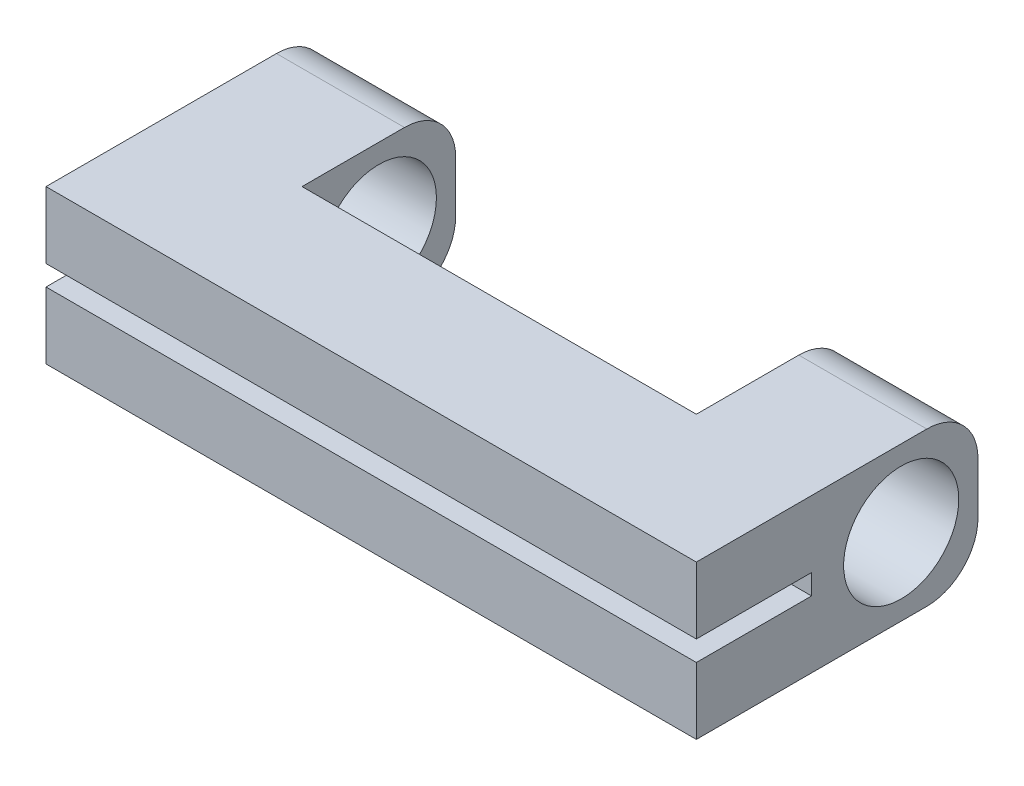
SolidWorks part; units mm, degrees
ref_plane "Front Plane" through (0, 0, 0) normal (0, 0, 1) x (1, 0, 0)
ref_plane "Top Plane" through (0, 0, 0) normal (0, 1, 0) x (1, 0, 0)
ref_plane "Right Plane" through (0, 0, 0) normal (1, 0, 0) x (0, 0, -1)
sketch "Sketch1" plane through (0, 0, 0) normal (0, 1, 0) x (1, 0, 0)
  line L1 (12.7, -2.5) -> (-12.7, -2.5)
  line L2 (12.7, -2.5) -> (12.7, 2.5)
  line L3 (12.7, 2.5) -> (-12.7, 2.5)
  line L4 (-12.7, -2.5) -> (-12.7, 2.5)
  line L5 (12.7, -2.5) -> (-12.7, 2.5) construction
  line L6 (12.7, 2.5) -> (-12.7, -2.5) construction
  point P0 (0, 0)
  dimension "D1" = 25.4
  dimension "D2" = 5
extrude "Boss-Extrude1" add sketch "Sketch1" along normal blind 6
sketch "Sketch2" plane through (12.7, 0, 0) normal (1, 0, 0) x (0, 0, -1)
  line L0 (-2.5, 6) -> (-2.5, 0) construction
  line L1 (-7, 2.6031) -> (2, 2.6031)
  line L2 (-7, 2.6031) -> (-7, 3.3969)
  line L3 (-7, 3.3969) -> (2, 3.3969)
  line L4 (2, 2.6031) -> (2, 3.3969)
  line L5 (-7, 2.6031) -> (2, 3.3969) construction
  line L6 (-7, 3.3969) -> (2, 2.6031) construction
  point P0 (-2.5, 3)
  dimension "D1" = 2
  dimension "D2" = 0.7937
extrude "Cut-Extrude1" cut sketch "Sketch2" against normal through all
sketch "Sketch3" plane through (0, 6, 0) normal (0, 1, 0) x (1, 0, 0)
  line L0 (6.35, 0) -> (-6.35, 0)
  point P4 (0, 0)
  dimension "D1" = 12.7
hole_wizard "M2 Clearance Hole1" positions "Sketch4" profile "Sketch5" hole size "M2" standard "ANSI Metric"
sketch "Sketch4" plane through (0, 6, 0) normal (0, 1, 0) x (1, 0, 0)
  point P0 (-6.35, 0)
  point P3 (6.35, 0)
sketch "Sketch5" plane through (-6.35, 6, 0) normal (1, 0, 0) x (0, 0, 1)
  line L0 (0, 0) -> (0, 6)
  line L1 (0, 6) -> (1.2, 6)
  line L2 (1.2, 6) -> (1.2, 0)
  line L5 (1.2, 0) -> (0, 0)
  line L11 (0, -6.35) -> (0, 107.95) construction
  dimension "Thru Hole Dia." = 2.4
  dimension "Thru Hole Depth" = 6
sketch "Sketch6" plane through (0, 0, -2.5) normal (0, 0, -1) x (-1, 0, 0)
  line L0 (-6.35, 6) -> (6.35, 6) construction
  line L1 (7.7, 0) -> (12.7, 0)
  line L2 (7.7, 0) -> (7.7, 6)
  line L3 (7.7, 6) -> (12.7, 6)
  line L4 (12.7, 0) -> (12.7, 6)
  line L5 (7.7, 0) -> (12.7, 6) construction
  line L6 (7.7, 6) -> (12.7, 0) construction
  line L7 (12.7, 6) -> (12.7, 0) construction
  point P0 (10.2, 3)
  dimension "D1" = 5
  dimension "D2" = 0
extrude "Boss-Extrude2" add sketch "Sketch6" along normal blind 6
sketch "Sketch7" plane through (-7.7, 0, 0) normal (1, 0, 0) x (0, 0, -1)
  line L0 (8.5, 6) -> (8.5, 0) construction
  line L2 (8.5, 6) -> (2.5, 6) construction
  point P0 (5.5, 3)
  point P3 (8.5, 3)
  point P6 (5.5, 6)
  dimension "D1" = 0
  dimension "D2" = 0
hole_wizard "#8 Clearance Hole1" positions "Sketch8" profile "Sketch9" hole size "#8" standard "ANSI Inch" end condition through all
sketch "Sketch8" plane through (-7.7, 0, 0) normal (1, 0, 0) x (0, 0, -1)
  point P0 (5.5, 3)
sketch "Sketch9" plane through (-7.7, 3, -5.5) normal (0, 1, 0) x (0, 0, -1)
  line L0 (0, 0) -> (0, 5)
  line L1 (0, 5) -> (2.2479, 5)
  line L2 (2.2479, 5) -> (2.2479, 0)
  line L5 (2.2479, 0) -> (0, 0)
  line L11 (0, -6.35) -> (0, 107.95) construction
  dimension "Thru Hole Dia." = 4.4958
  dimension "Thru Hole Depth" = 5
fillet "Fillet1" radius 2 2 edges at (-10.2, 0, -8.5) (-10.2, 6, -8.5)
mirror "Mirror1" about plane through (0, 0, 0) normal (1, 0, 0) of bodies 105
